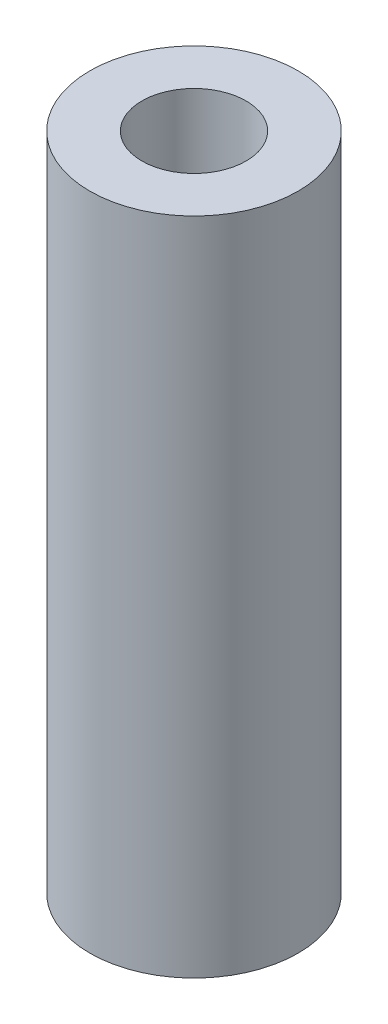
SolidWorks part; units mm, degrees
ref_plane "Front Plane" through (0, 0, 0) normal (0, 0, 1) x (1, 0, 0)
ref_plane "Top Plane" through (0, 0, 0) normal (0, 1, 0) x (1, 0, 0)
ref_plane "Right Plane" through (0, 0, 0) normal (1, 0, 0) x (0, 0, -1)
sketch "Sketch1" plane through (0, 0, 0) normal (0, 1, 0) x (1, 0, 0)
  circle A0 centre (0, 0) radius 3
  circle A1 centre (0, 0) radius 1.5
  dimension "D1" = 6
  dimension "D2" = 3
extrude "Boss-Extrude1" add sketch "Sketch1" along normal blind 19
